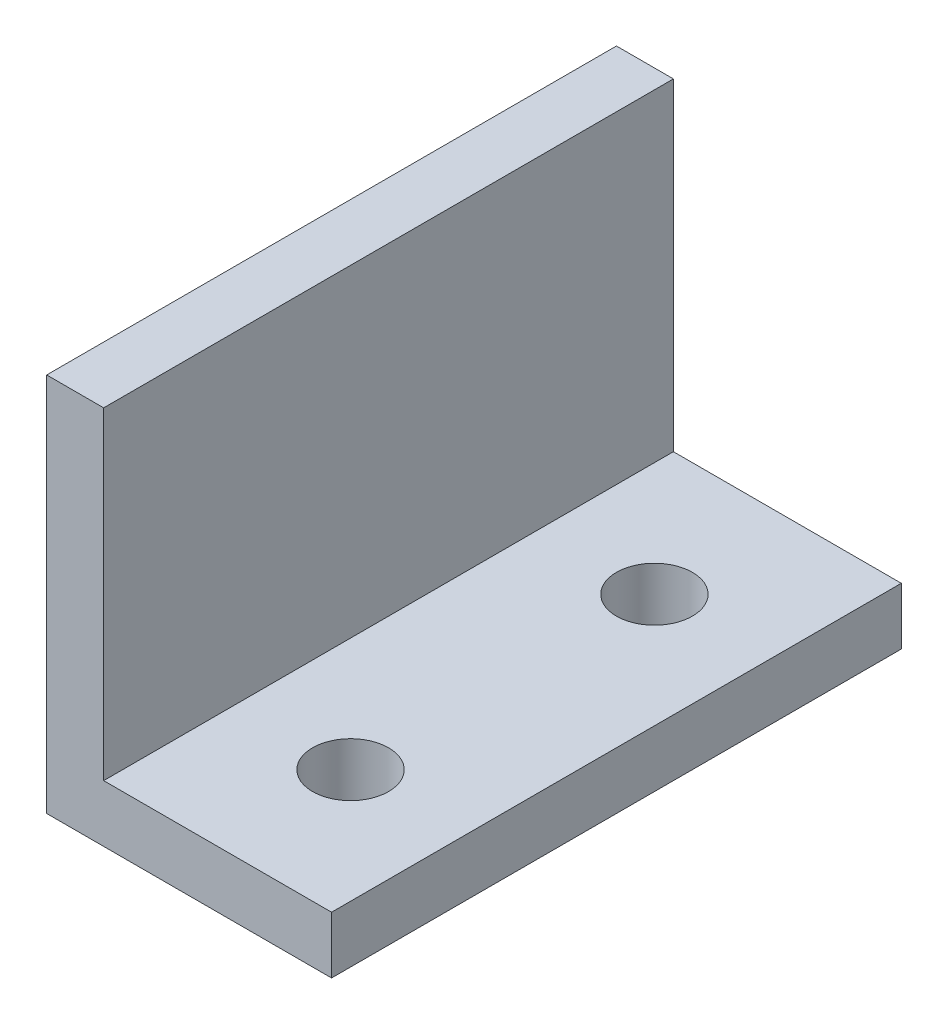
SolidWorks part; units mm, degrees
ref_plane "Front Plane" through (0, 0, 0) normal (0, 0, 1) x (1, 0, 0)
ref_plane "Top Plane" through (0, 0, 0) normal (0, 1, 0) x (1, 0, 0)
ref_plane "Right Plane" through (0, 0, 0) normal (1, 0, 0) x (0, 0, -1)
sketch "Sketch1" plane through (0, 0, 0) normal (0, 0, 1) x (1, 0, 0)
  line L0 (0, 0) -> (0, 20)
  line L1 (0, 20) -> (3, 20)
  line L2 (0, 0) -> (15, 0)
  line L3 (15, 0) -> (15, 3)
  line L4 (15, 3) -> (3, 3)
  line L5 (3, 3) -> (3, 20)
  dimension "D1" = 20
  dimension "D2" = 15
  dimension "D3" = 3
  dimension "D4" = 3
extrude "Boss-Extrude1" add sketch "Sketch1" along normal blind 30
sketch "Sketch2" plane through (0, 3, 0) normal (0, 1, 0) x (1, 0, 0)
  line L0 (15, 0) -> (3, 0) construction
  circle A0 centre (9, -7) radius 2
  circle A2 centre (9, -23) radius 2
  dimension "D1" = 7
extrude "Cut-Extrude1" cut sketch "Sketch2" against normal blind 3
